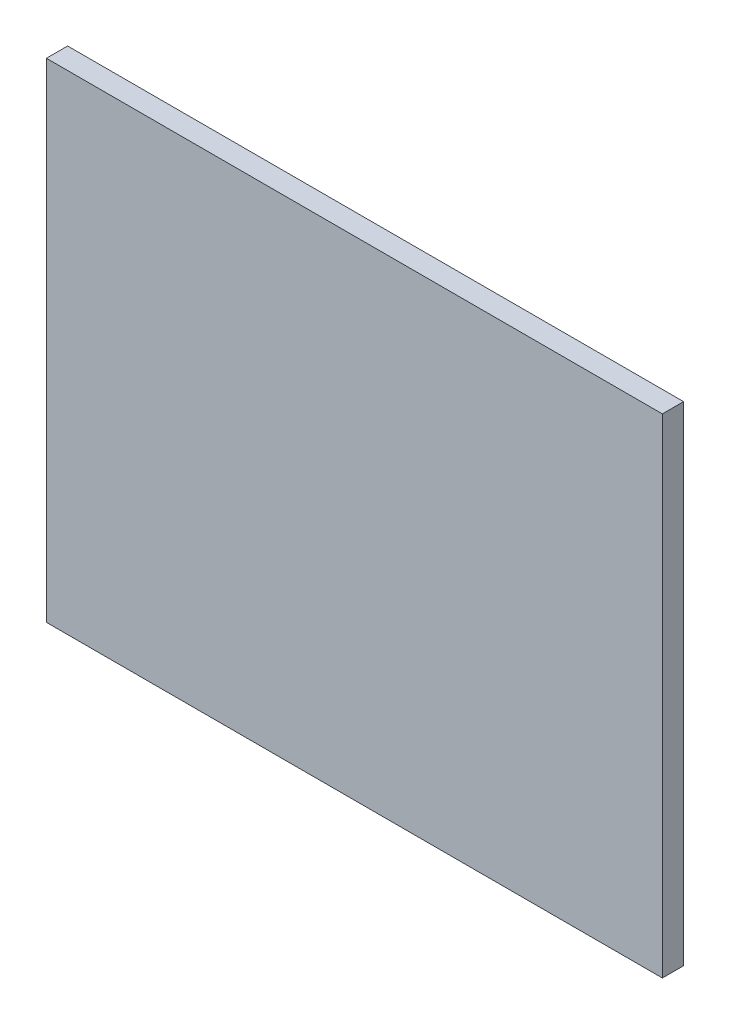
SolidWorks part; units mm, degrees
ref_plane "前视基准面" through (0, 0, 0) normal (0, 0, 1) x (1, 0, 0)
ref_plane "上视基准面" through (0, 0, 0) normal (0, 1, 0) x (1, 0, 0)
ref_plane "右视基准面" through (0, 0, 0) normal (1, 0, 0) x (0, 0, -1)
sketch "草图1" plane through (0, 0, 0) normal (0, 0, 1) x (1, 0, 0)
  line L1 (0, 0) -> (290, 0)
  line L2 (0, 0) -> (0, 230)
  line L3 (0, 230) -> (290, 230)
  line L4 (290, 0) -> (290, 230)
  dimension "D1" = 230
  dimension "D2" = 290
extrude "凸台-拉伸1" add sketch "草图1" along normal blind 10
sketch "草图7" plane through (0, 0, 0) normal (0, 0, -1) x (-1, 0, 0)
  line L0 (-15, 15) -> (-15, 215)
  line L1 (-15, 215) -> (-275, 215)
  line L2 (-275, 215) -> (-275, 15)
  line L3 (-275, 15) -> (-15, 15)
  line L4 (0, 0) -> (0, 230)
  line L5 (0, 230) -> (-290, 230)
  line L6 (-290, 230) -> (-290, 0)
  line L7 (-290, 0) -> (0, 0)
  line L8 (0, 0) -> (0, 230)
  line L9 (0, 230) -> (-290, 230)
  line L10 (-290, 230) -> (-290, 0)
  line L11 (-290, 0) -> (0, 0)
  dimension "D1" = 0
  dimension "D2" = 15
extrude "凸台-拉伸2" add sketch "草图7" along normal blind 10 contours L2 L3 L0 L1
